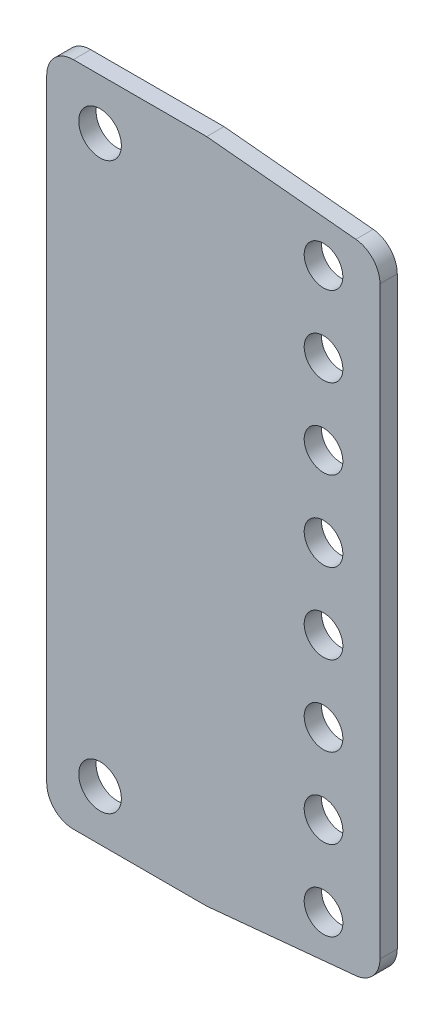
SolidWorks part; units mm, degrees
material "6061-T6 (SS)"
ref_plane "Front Plane" through (0, 0, 0) normal (0, 0, 1) x (1, 0, 0)
ref_plane "Top Plane" through (0, 0, 0) normal (0, 1, 0) x (1, 0, 0)
ref_plane "Right Plane" through (0, 0, 0) normal (1, 0, 0) x (0, 0, -1)
sketch "Sketch1" plane through (0, 0, 0) normal (0, 0, 1) x (1, 0, 0)
  line L0 (12, 50) -> (25, 48.75)
  line L1 (0, 0) -> (12, 0)
  line L2 (0, 0) -> (0, 50)
  line L3 (0, 50) -> (12, 50)
  line L4 (25, 1.25) -> (25, 48.75)
  line L5 (12, 0) -> (25, 1.25)
  line L6 (4, 46.2132) -> (4, 3.7868) construction
  line L7 (20.7668, 46) -> (20.7668, 4) construction
  line L8 (20.7668, 46) -> (20.7668, 40) construction
  circle A0 centre (4, 46.2132) radius 1.6
  circle A1 centre (4, 3.7868) radius 1.6
  circle A2 centre (20.7668, 46) radius 1.45
  circle A3 centre (20.7668, 4) radius 1.45
  circle A4 centre (20.7668, 40) radius 1.45
  circle A5 centre (20.7668, 34) radius 1.45
  circle A6 centre (20.7668, 28) radius 1.45
  circle A7 centre (20.7668, 22) radius 1.45
  circle A8 centre (20.7668, 16) radius 1.45
  circle A9 centre (20.7668, 10) radius 1.45
  point P11 (4, 25)
  point P12 (0, 25)
  point P17 (20.7668, 25)
  point P18 (25, 25)
  dimension "D2" = 3.2
  dimension "D6" = 2.9
  dimension "D1" = 50
  dimension "D3" = 42.4264
  dimension "D4" = 4
  dimension "D5" = 42
  dimension "D7" = 16.7668
  dimension "D8" = 47.5
  dimension "D9" = 25
  dimension "D10" = 12
  dimension "D12" = 6
  dimension "D11" = 7
extrude "Boss-Extrude1" add sketch "Sketch1" along normal blind 1.3
fillet "Fillet1" radius 2 4 edges at (25, 48.75, 0.65) (25, 1.25, 0.65) (0, 0, 0.65) (0, 50, 0.65)
